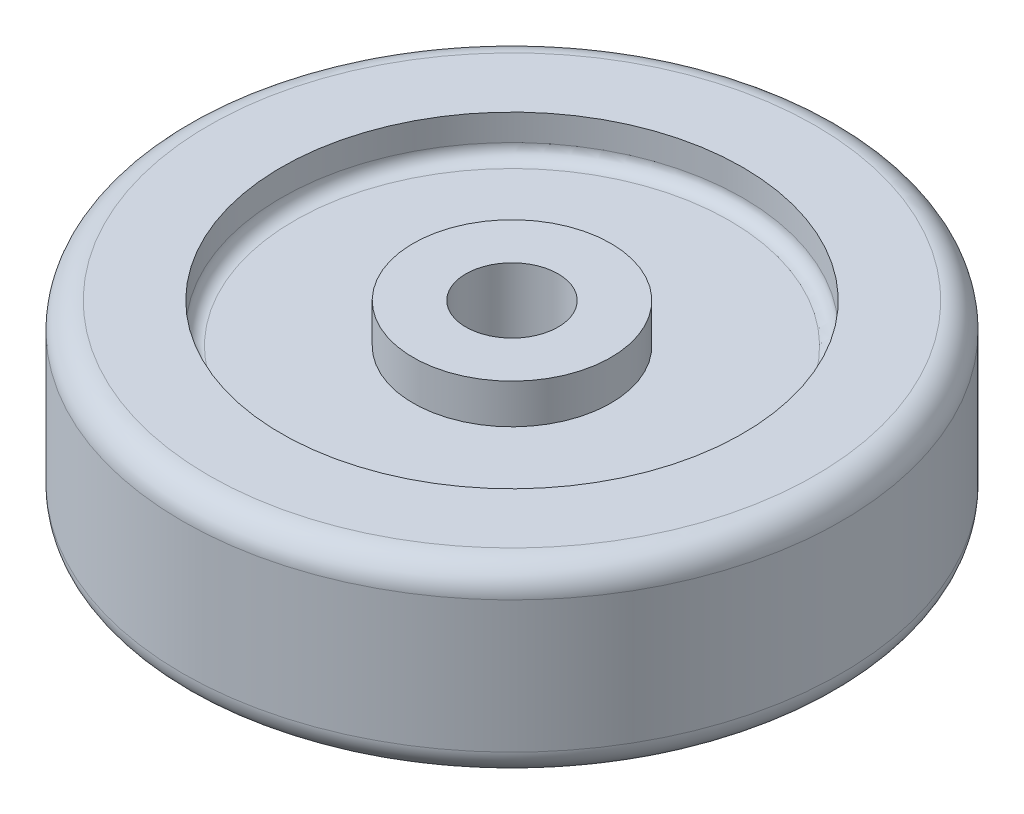
SolidWorks part; units mm, degrees
ref_plane "Front" through (0, 0, 0) normal (0, 0, 1) x (1, 0, 0)
ref_plane "Top" through (0, 0, 0) normal (0, 1, 0) x (1, 0, 0)
ref_plane "Right" through (0, 0, 0) normal (1, 0, 0) x (0, 0, -1)
sketch "草图1" plane through (0, 0, 0) normal (0, 0, 1) x (1, 0, 0)
  line L0 (-50, -14) -> (-50, 14)
  line L1 (-50, 14) -> (-35, 14)
  line L2 (-35, 14) -> (-35, 8)
  line L3 (-35, 8) -> (-15, 8)
  line L4 (-15, 8) -> (-15, 14)
  line L5 (-15, 14) -> (-7, 14)
  line L6 (-7, 14) -> (-7, -14)
  line L8 (0, 0) -> (0, 27.6266) construction
  line L9 (-15, -14) -> (-7, -14)
  line L10 (-15, -8) -> (-15, -14)
  line L11 (-35, -8) -> (-15, -8)
  line L12 (-35, -14) -> (-35, -8)
  line L13 (-50, -14) -> (-35, -14)
  dimension "D2" = 6
  dimension "D3" = 15
  dimension "D4" = 7
  dimension "D5" = 50
  dimension "D6" = 35
revolve "旋转1" add sketch "草图1" angle 360 about L8
fillet "圆角1" radius 4 2 edges at (0, -14, -50) (0, 14, -50)
fillet "圆角2" radius 2 1 edges at (0, 8, -35)
